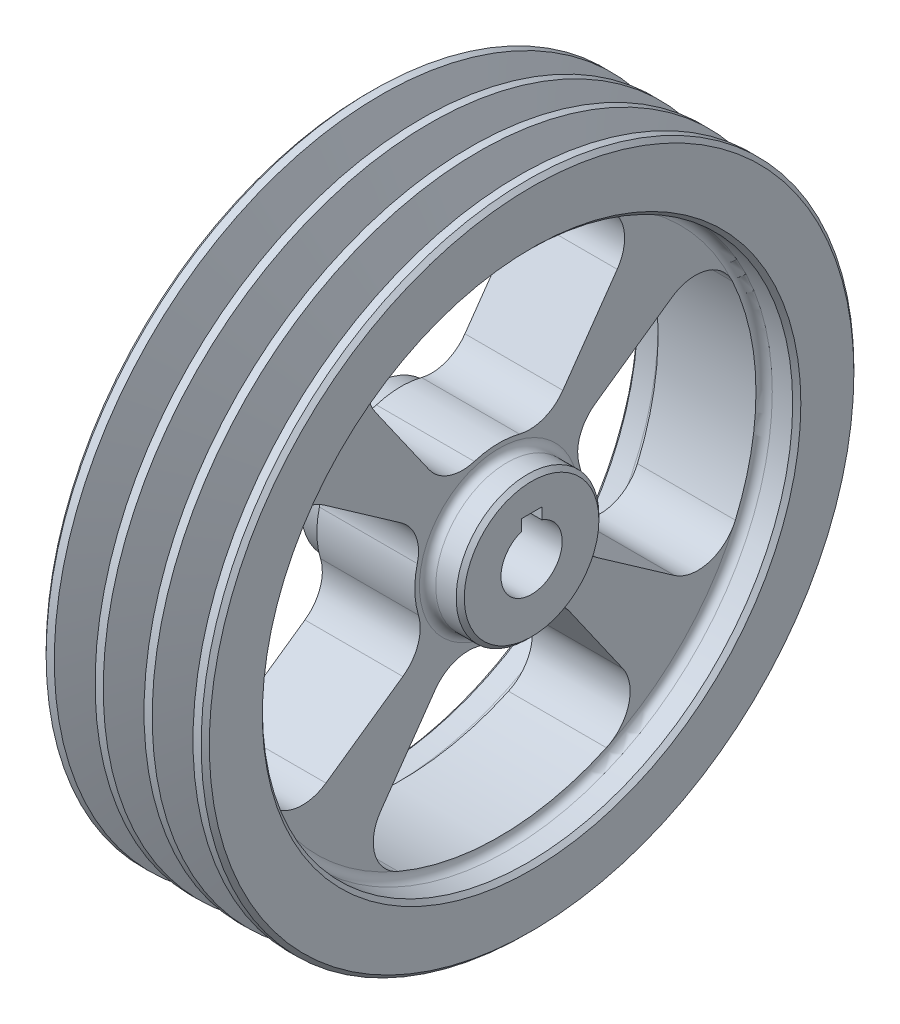
SolidWorks part; units mm, degrees
material "Alloy Steel (SS)"
ref_plane "Front Plane" through (0, 0, 0) normal (0, 0, 1) x (1, 0, 0)
ref_plane "Top Plane" through (0, 0, 0) normal (0, 1, 0) x (1, 0, 0)
ref_plane "Right Plane" through (0, 0, 0) normal (1, 0, 0) x (0, 0, -1)
sketch "Sketch1" plane through (0, 0, 0) normal (0, 1, 0) x (1, 0, 0)
  line L0 (-12, 17.5) -> (-12, 65)
  line L1 (-12, 65) -> (-20, 65)
  line L2 (-20, 65) -> (-20, 80)
  line L3 (-20, 80) -> (-17, 80)
  line L4 (-17, 80) -> (-13.9427, 70)
  line L5 (-13.9427, 70) -> (-10.0573, 70)
  line L6 (-10.0573, 70) -> (-7, 80)
  line L7 (-7, 80) -> (-5, 80)
  line L8 (7, 80) -> (10.0573, 70)
  line L9 (10.0573, 70) -> (13.9427, 70)
  line L10 (13.9427, 70) -> (17, 80)
  line L11 (17, 80) -> (20, 80)
  line L12 (20, 80) -> (20, 65)
  line L13 (20, 65) -> (12, 65)
  line L14 (12, 65) -> (12, 17.5)
  line L15 (12, 17.5) -> (20, 17.5)
  line L16 (20, 17.5) -> (20, 7.5)
  line L17 (20, 7.5) -> (-20, 7.5)
  line L18 (-20, 7.5) -> (-20, 17.5)
  line L19 (-20, 17.5) -> (-12, 17.5)
  line L20 (0, 0) -> (0, 100) construction
  line L21 (0, 0) -> (-66.9649, 0) construction
  line L22 (-5, 80) -> (-1.9427, 70)
  line L23 (-12, 168.8945) -> (-12, 92.485) construction
  line L24 (12, 168.8945) -> (12, 92.485) construction
  line L25 (-1.9427, 70) -> (1.9427, 70)
  line L26 (1.9427, 70) -> (5, 80)
  line L27 (5, 80) -> (7, 80)
  point P27 (0, 70)
  point P32 (0, 0)
  dimension "D1" = 10
  dimension "D2" = 10
  dimension "D3" = 14
  dimension "D4" = 10
  dimension "D5" = 10
  dimension "D6" = 34
  dimension "D7" = 8
  dimension "D8" = 10
  dimension "D9" = 3
  dimension "D10" = 34
  dimension "D11" = 7.5
  dimension "D12" = 40
  dimension "D14" = 100
  dimension "D15" = 15
  dimension "D16" = 15
  dimension "D17" = 34
  dimension "D18" = 10
revolve "Revolve1" add sketch "Sketch1" angle 360 about L21
fillet "Fillet1" radius 2 4 edges at (12, 0, -65) (-12, 0, -17.5) (-12, 0, -65) (12, 0, -17.5)
chamfer "Chamfer1" distance 1 angle 45 6 edges at (20, 0, -17.5) (20, 0, -65) (20, 0, -80) (-20, 0, -80) (-20, 0, -17.5) (-20, 0, -65)
sketch "Sketch4" plane through (12, 0, 0) normal (1, 0, 0) x (0, 0, -1)
  line L0 (-17.1535, 23.5615) -> (-30.351, 42.4094)
  line L1 (15.6635, 23.9764) -> (28.9923, 43.0118)
  line L2 (0, 0) -> (0, 64.8735) construction
  arc A7 (5.0332, 20.0141) -> (-6.0368, 19.7346) centre (0, 0) ccw
  arc A8 (24.7254, 57.9453) -> (-26.3405, 57.2292) centre (0, 0) ccw
  arc A9 (-6.0368, 19.7346) -> (-17.1535, 23.5615) centre (-8.962, 29.2972) cw
  arc A10 (5.0332, 20.0141) -> (15.6635, 23.9764) centre (7.472, 29.7122) ccw
  arc A11 (28.9923, 43.0118) -> (24.7254, 57.9453) centre (20.8008, 48.7476) ccw
  arc A12 (-30.351, 42.4094) -> (-26.3405, 57.2292) centre (-22.1594, 48.1452) cw
  circle A13 centre (0, 0) radius 63 construction
  point P13 (0, 0)
  point P16 (0, 0)
  dimension "D1" = 10
  dimension "D2" = 70
  dimension "D3" = 35
extrude "Cut-Extrude1" cut sketch "Sketch4" against normal blind 40
pattern_circular "CirPattern1" count 4 every 90 about axis through (0, 0, 0) along (1, 0, 0) of "Cut-Extrude1"
sketch "Sketch5" plane through (20, 0, 0) normal (1, 0, 0) x (0, 0, -1)
  line L6 (-2.5, 9.8) -> (2.5, 9.8)
  line L9 (-2.5, 9.8) -> (-2.5, 4.8)
  line L10 (-2.5, 4.8) -> (2.5, 4.8)
  line L11 (2.5, 9.8) -> (2.5, 4.8)
  point P4 (0, 0)
  point P5 (0, 4.8)
  dimension "D1" = 5
  dimension "D2" = 5
  dimension "D3" = 9.8
extrude "Cut-Extrude2" cut sketch "Sketch5" against normal through all
